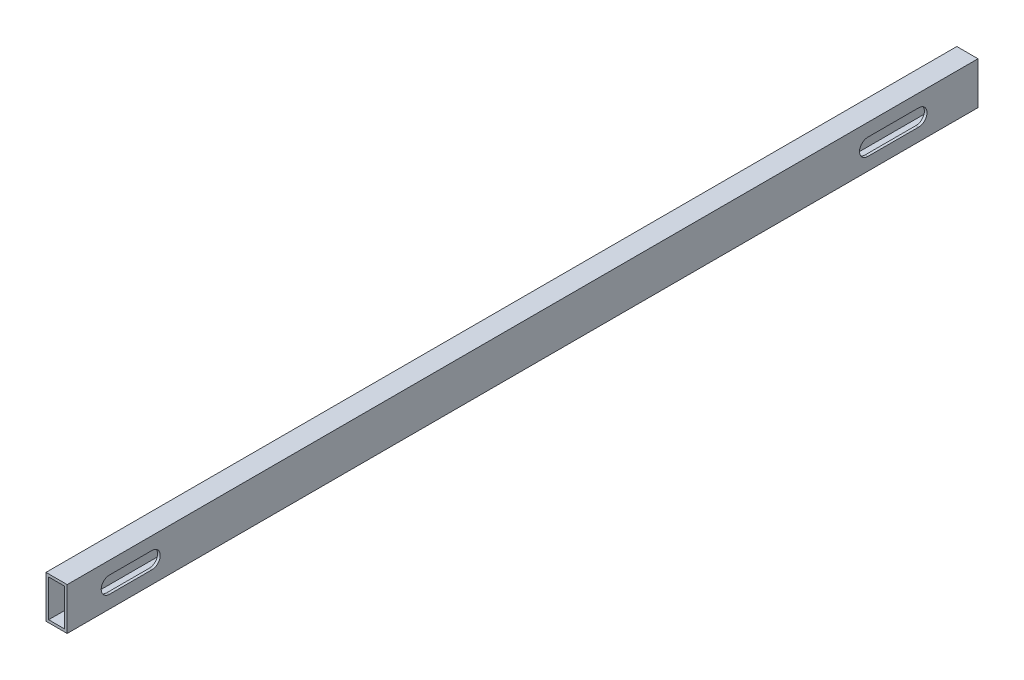
SolidWorks part; units mm, degrees
ref_plane "Front Plane" through (0, 0, 0) normal (0, 0, 1) x (1, 0, 0)
ref_plane "Top Plane" through (0, 0, 0) normal (0, 1, 0) x (1, 0, 0)
ref_plane "Right Plane" through (0, 0, 0) normal (1, 0, 0) x (0, 0, -1)
sketch "Sketch1" plane through (0, 0, 0) normal (0, 0, 1) x (1, 0, 0)
  line L1 (-6.35, -12.7) -> (6.35, -12.7)
  line L2 (-6.35, -12.7) -> (-6.35, 12.7)
  line L3 (-6.35, 12.7) -> (6.35, 12.7)
  line L4 (6.35, -12.7) -> (6.35, 12.7)
  line L6 (-6.35, 12.7) -> (6.35, -12.7) construction
  line L7 (-4.7625, -11.1125) -> (4.7625, -11.1125)
  line L8 (-4.7625, -11.1125) -> (-4.7625, 11.1125)
  line L9 (-4.7625, 11.1125) -> (4.7625, 11.1125)
  line L10 (4.7625, -11.1125) -> (4.7625, 11.1125)
  line L11 (-4.7625, -11.1125) -> (4.7625, 11.1125) construction
  line L12 (-4.7625, 11.1125) -> (4.7625, -11.1125) construction
  point P0 (0, 0)
  point P6 (0, 0)
  dimension "D1" = 25.4
  dimension "D2" = 1.5875
  dimension "D3" = 12.7
  dimension "D4" = 1.5875
  dimension "D5" = 1.5875
extrude "Boss-Extrude1" add sketch "Sketch1" along normal blind 546.1
sketch "Sketch2" plane through (6.35, 0, 0) normal (1, 0, 0) x (0, 0, -1)
  line L0 (-546.1, 0) -> (0, 0) construction
  line L1 (-546.1, -12.7) -> (-546.1, 12.7) construction
  line L2 (-508, 12.7) -> (-508, -12.7) construction
  line L3 (-44.45, 0) -> (-57.15, 0) construction
  line L4 (-44.45, -3.302) -> (-57.15, -3.302)
  line L5 (-44.45, 3.302) -> (-57.15, 3.302)
  line L6 (-546.1, 12.7) -> (0, 12.7) construction
  line L7 (-546.1, -12.7) -> (0, -12.7) construction
  line L8 (-50.8, 12.7) -> (-50.8, -12.7) construction
  circle A0 centre (-508, 0) radius 3.81
  arc A2 (-44.45, -3.302) -> (-44.45, 3.302) centre (-44.45, 0) ccw
  arc A3 (-57.15, 3.302) -> (-57.15, -3.302) centre (-57.15, 0) ccw
  circle A4 centre (-520.7, 0) radius 2.75
  circle A5 centre (-495.3, 0) radius 2.75
  point P9 (-50.8, 0)
  dimension "D1" = 7.62
  dimension "D2" = 3.302
  dimension "D6" = 5.5
  dimension "D3" = 38.1
  dimension "D4" = 12.7
  dimension "D5" = 457.2
  dimension "D7" = 25.4
extrude "Cut-Extrude1" cut sketch "Sketch2" against normal through all
sketch "Sketch3" plane through (0, 0, 546.1) normal (0, 0, 1) x (1, 0, 0)
  line L0 (-6.35, 12.7) -> (-6.35, -12.7) construction
  line L1 (-4.7625, 11.1125) -> (-6.35, 11.1125)
  line L2 (-4.7625, 11.1125) -> (-4.7625, -11.1125)
  line L3 (-4.7625, -11.1125) -> (-6.35, -11.1125)
  line L4 (-6.35, 11.1125) -> (-6.35, -11.1125)
  line L5 (-4.7625, -11.1125) -> (4.7625, -11.1125) construction
sketch "Sketch4" plane through (6.35, 0, 0) normal (-1, 0, 0) x (0, 0, 1)
  line L0 (35.56, 0) -> (66.04, 0) construction
  line L1 (35.56, 5) -> (66.04, 5)
  line L2 (35.56, -5) -> (66.04, -5)
  line L3 (495.3, 0) -> (520.7, 0) construction
  line L4 (495.3, 5) -> (520.7, 5)
  line L5 (495.3, -5) -> (520.7, -5)
  arc A0 (35.56, 5) -> (35.56, -5) centre (35.56, 0) ccw
  arc A1 (66.04, -5) -> (66.04, 5) centre (66.04, 0) ccw
  arc A2 (495.3, 5) -> (495.3, -5) centre (495.3, 0) ccw
  arc A3 (520.7, -5) -> (520.7, 5) centre (520.7, 0) ccw
  point P2 (50.8, 0)
  point P13 (508, 0)
  dimension "D1" = 5
extrude "Cut-Extrude3" cut sketch "Sketch4" along normal up to next
sketch "Sketch5" plane through (0, -12.7, 0) normal (0, -1, 0) x (1, 0, 0)
  line L0 (-6.35, 546.1) -> (6.35, 546.1) construction
  line L1 (0, 546.1) -> (0, 0) construction
  line L2 (-6.35, 273.05) -> (6.35, 273.05) construction
  line L3 (-6.35, 546.1) -> (-6.35, 0) construction
  line L4 (6.35, 546.1) -> (6.35, 0) construction
  circle A0 centre (0, 533.4) radius 2.75
  circle A1 centre (0, 12.7) radius 2.75
  dimension "D1" = 5.5
  dimension "D2" = 12.7
extrude "Cut-Extrude5" cut sketch "Sketch5" against normal up to next
